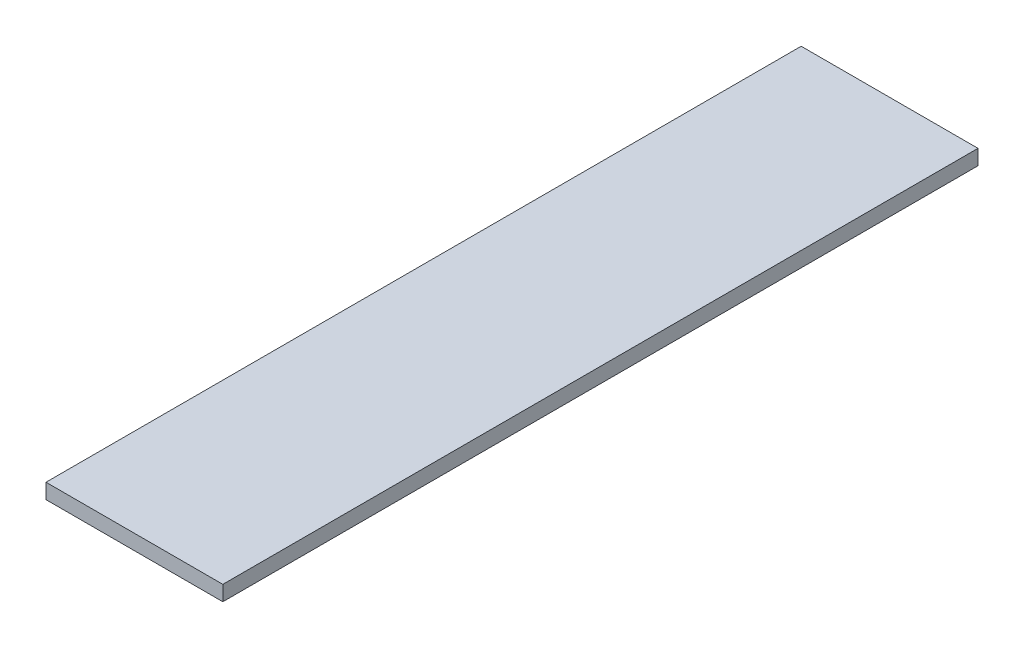
SolidWorks part; units mm, degrees
ref_plane "Front Plane" through (0, 0, 0) normal (0, 0, 1) x (1, 0, 0)
ref_plane "Top Plane" through (0, 0, 0) normal (0, 1, 0) x (1, 0, 0)
ref_plane "Right Plane" through (0, 0, 0) normal (1, 0, 0) x (0, 0, -1)
sketch "Sketch1" plane through (0, 0, 0) normal (0, 0, 1) x (1, 0, 0)
  line L4 (-5.8542, 55.6986) -> (-5.8542, 56.6986)
  line L5 (28.0027, 48.5021) -> (17.3066, 53.2643)
  line L6 (17.3066, 53.2643) -> (5.8542, 55.6986)
  line L7 (5.8542, 55.6986) -> (-5.8542, 55.6986)
  line L8 (-5.8542, 55.6986) -> (-17.3066, 53.2643)
  line L9 (-17.3066, 53.2643) -> (-28.0027, 48.5021)
  line L10 (-28.0027, 48.5021) -> (-37.4749, 41.6201)
  line L11 (-37.4749, 41.6201) -> (-45.3093, 32.9191)
  line L12 (-45.3093, 32.9191) -> (-51.1635, 22.7794)
  line L13 (-51.1635, 22.7794) -> (-54.7815, 11.6442)
  line L14 (-54.7815, 11.6442) -> (-56.0054, 0)
  line L15 (-56.0054, 0) -> (-54.7815, -11.6442)
  line L16 (-54.7815, -11.6442) -> (-51.1635, -22.7794)
  line L17 (-51.1635, -22.7794) -> (-45.3093, -32.9191)
  line L18 (-45.3093, -32.9191) -> (-37.4749, -41.6201)
  line L19 (-37.4749, -41.6201) -> (-28.0027, -48.5021)
  line L20 (-28.0027, -48.5021) -> (-17.3066, -53.2643)
  line L21 (-17.3066, -53.2643) -> (-5.8542, -55.6986)
  line L22 (-5.8542, -55.6986) -> (5.8542, -55.6986)
  line L23 (5.8542, -55.6986) -> (17.3066, -53.2643)
  line L24 (17.3066, -53.2643) -> (28.0027, -48.5021)
  line L25 (28.0027, -48.5021) -> (37.4749, -41.6201)
  line L26 (37.4749, -41.6201) -> (45.3093, -32.9191)
  line L27 (45.3093, -32.9191) -> (51.1635, -22.7794)
  line L28 (51.1635, -22.7794) -> (54.7815, -11.6442)
  line L29 (54.7815, -11.6442) -> (56.0054, 0)
  line L30 (56.0054, 0) -> (54.7815, 11.6442)
  line L31 (54.7815, 11.6442) -> (51.1635, 22.7794)
  line L32 (51.1635, 22.7794) -> (45.3093, 32.9191)
  line L33 (45.3093, 32.9191) -> (37.4749, 41.6201)
  line L34 (37.4749, 41.6201) -> (28.0027, 48.5021)
  line L35 (-5.8542, 56.6986) -> (5.8542, 56.6986)
  line L36 (5.8542, 56.6986) -> (5.8542, 55.6986)
  circle A1 centre (0, 0) radius 55.6986 construction
  point P2 (0, 0)
  point P3 (0, 0)
  point P5 (0, 0)
  point P7 (36.188, 125.2083)
  point P40 (27.7503, 119.7382)
  dimension "D1" = 1
  dimension "D2" = 57
extrude "Boss-Extrude1" add sketch "Sketch1" along normal mid plane 50 contours L36 L35 L4 L7
